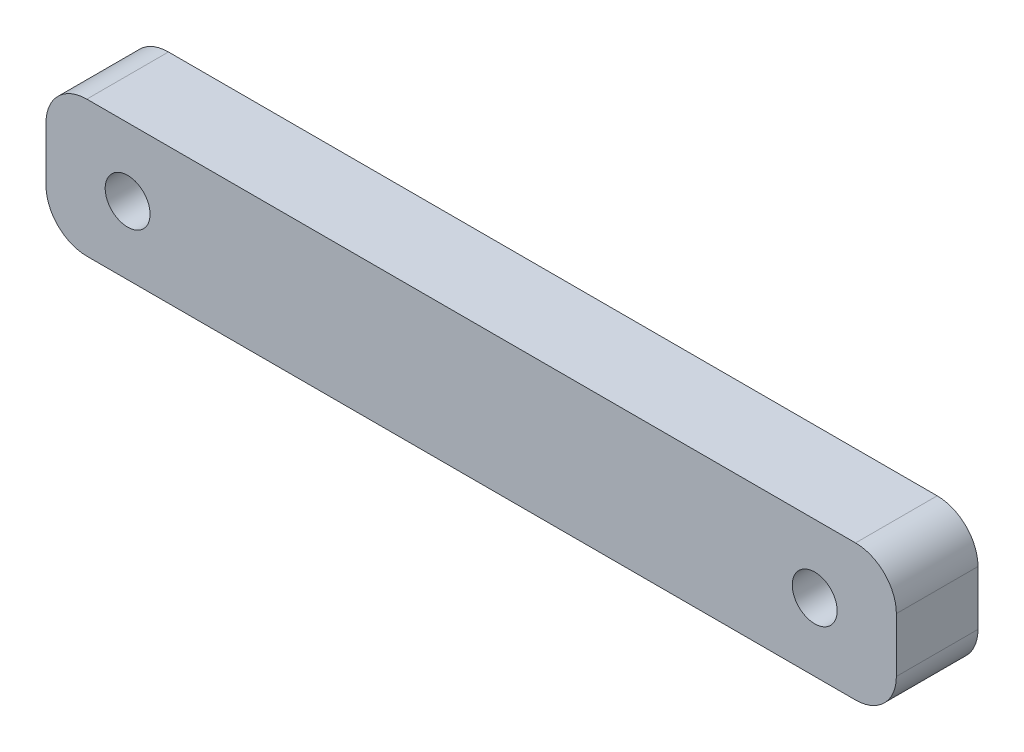
SolidWorks part; units mm, degrees
ref_plane "Front" through (0, 0, 0) normal (0, 0, 1) x (1, 0, 0)
ref_plane "Top" through (0, 0, 0) normal (0, 1, 0) x (1, 0, 0)
ref_plane "Right" through (0, 0, 0) normal (1, 0, 0) x (0, 0, -1)
sketch "Sketch1" plane through (0, 0, 0) normal (0, 0, 1) x (1, 0, 0)
  line L1 (0, 0) -> (62.5, 0)
  line L2 (0, 0) -> (0, -10)
  line L3 (0, -10) -> (62.5, -10)
  line L4 (62.5, 0) -> (62.5, -10)
  dimension "D1" = 10
  dimension "D2" = 62.5
extrude "Boss-Extrude1" add sketch "Sketch1" along normal blind 6
sketch "Sketch2" plane through (0, 0, 6) normal (0, 0, 1) x (1, 0, 0)
  line L0 (0, 0) -> (0, -10) construction
  line L1 (62.5, -10) -> (62.5, 0) construction
  circle A0 centre (56.5, -5) radius 1.65
  circle A1 centre (6, -5) radius 1.65
  dimension "D1" = 3.3
  dimension "D2" = 3.3
  dimension "D3" = 6
  dimension "D4" = 6
extrude "Cut-Extrude1" cut sketch "Sketch2" against normal through all
fillet "Fillet1" radius 3 4 edges at (62.5, -10, 3) (62.5, 0, 3) (0, -10, 3) (0, 0, 3)
equation "\"滑动-垂直孔\" = 0.6"
equation "\"滑动-水平孔\"= 0.3"
equation "\"松动-垂直孔\" = 0.3"
equation "\"松动-水平孔\"= 0.1"
equation "\"正常-垂直孔\" = 0.15"
equation "\"正常-水平孔\"= 0"
equation "\"紧缩-垂直孔\"= 0"
equation "\"紧缩-水平孔\"= - 0.1"
equation "\"D1@Sketch2\"=\"松动-垂直孔\"+3"
equation "\"D2@Sketch2\"=\"松动-垂直孔\"+3"
